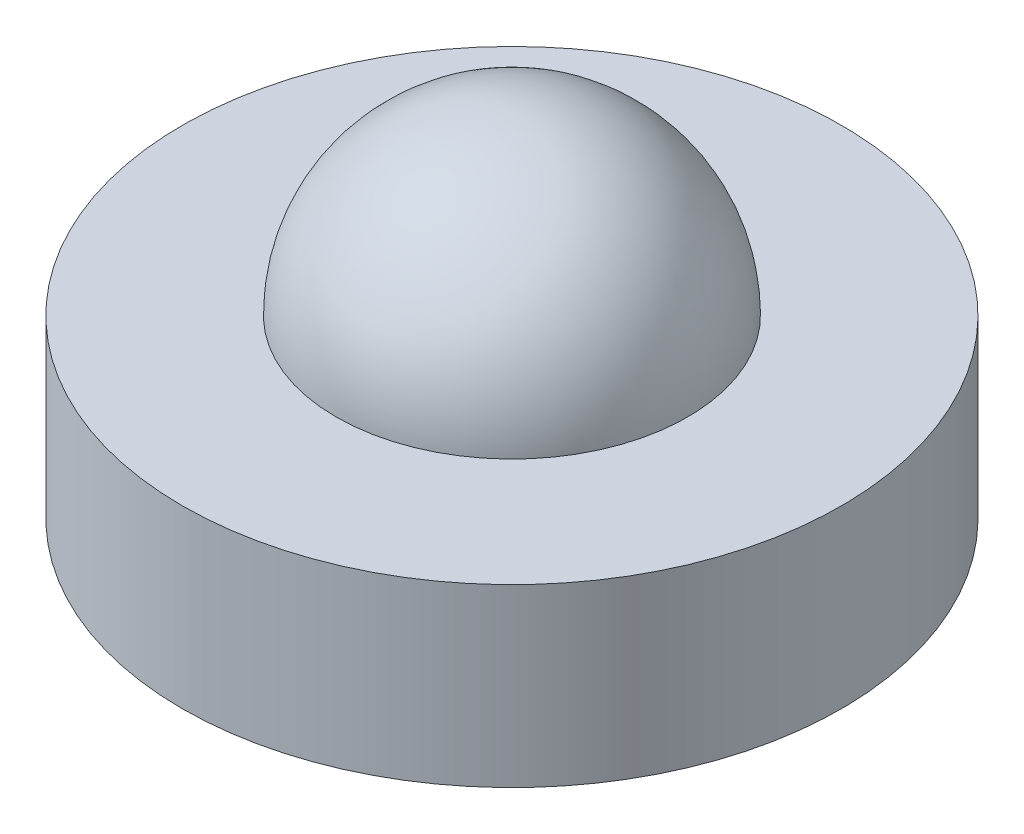
SolidWorks part; units mm, degrees
ref_plane "Front Plane" through (0, 0, 0) normal (0, 0, 1) x (1, 0, 0)
ref_plane "Top Plane" through (0, 0, 0) normal (0, 1, 0) x (1, 0, 0)
ref_plane "Right Plane" through (0, 0, 0) normal (1, 0, 0) x (0, 0, -1)
sketch "Sketch1" plane through (0, 0, 0) normal (0, 1, 0) x (1, 0, 0)
  circle A0 centre (0, 0) radius 3.75
extrude "Boss-Extrude1" add sketch "Sketch1" along normal blind 2
sketch "Sketch2" plane through (0, 2, 0) normal (0, 1, 0) x (1, 0, 0)
  line L0 (2.864, 0) -> (7.0461, 0) construction
  line L1 (-2, 0) -> (2, 0)
  arc A0 (2, 0) -> (-2, 0) centre (0, 0) ccw
revolve "Revolve6" add sketch "Sketch2" angle 360 about L0
sketch "Sketch3" plane through (0, 0, 0) normal (0, 0, 1) x (1, 0, 0)
  line L0 (-2, 2) -> (2, 2)
  line L1 (3.75, 2) -> (-3.75, 2) construction
  line L2 (2, 2) -> (2, 0)
  line L3 (-3.75, 0) -> (3.75, 0) construction
  line L4 (2, 0) -> (-2, 0)
  line L5 (-2, 0) -> (-2, 2)
  circle A0 centre (0, 2) radius 2 construction
extrude "Cut-Extrude1" cut sketch "Sketch3" against normal through all and the other way through all
